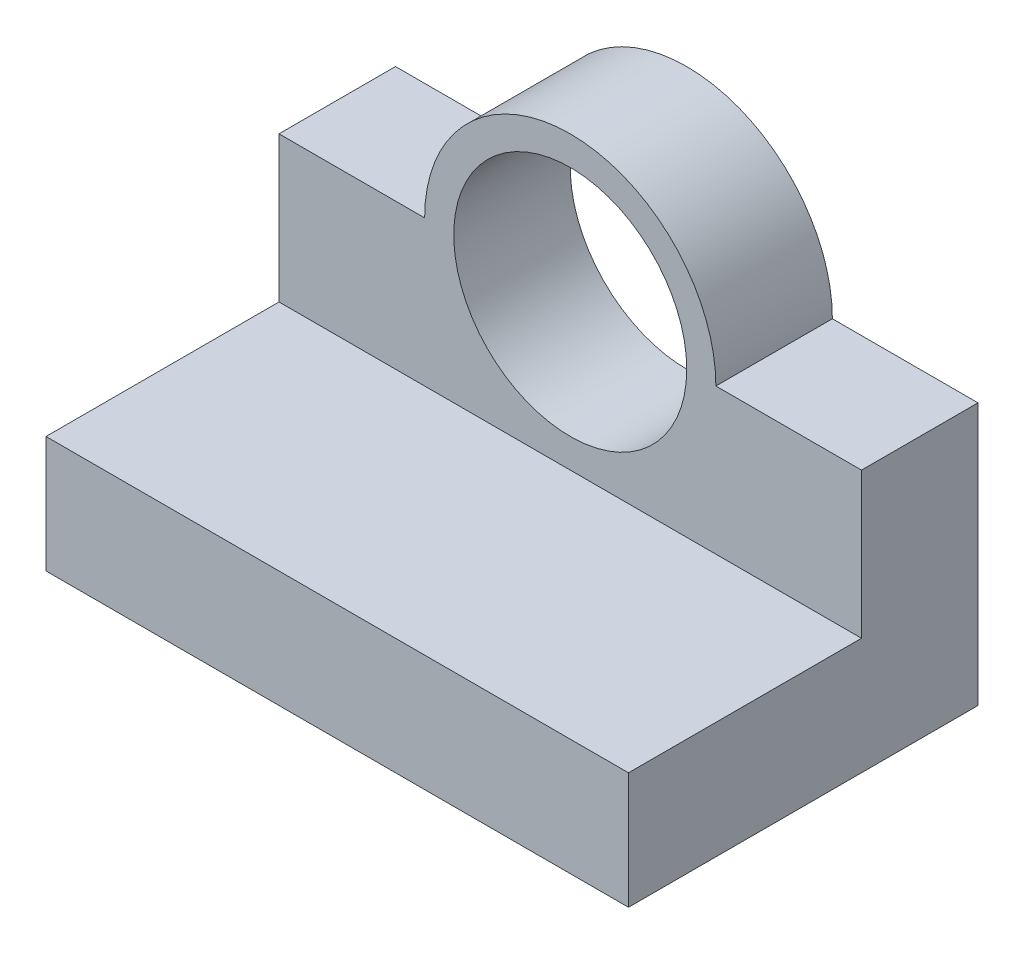
SolidWorks part; units mm, degrees
ref_plane "Front Plane" through (0, 0, 0) normal (0, 0, 1) x (1, 0, 0)
ref_plane "Top Plane" through (0, 0, 0) normal (0, 1, 0) x (1, 0, 0)
ref_plane "Right Plane" through (0, 0, 0) normal (1, 0, 0) x (0, 0, -1)
sketch "Sketch2" plane through (0, 0, 0) normal (0, 1, 0) x (1, 0, 0)
  line L1 (-50, 30) -> (50, 30)
  line L2 (-50, 30) -> (-50, -30)
  line L3 (-50, -30) -> (50, -30)
  line L4 (50, 30) -> (50, -30)
  line L5 (-50, 30) -> (50, -30) construction
  line L6 (-50, -30) -> (50, 30) construction
  point P0 (0, 0)
  dimension "D1" = 60
  dimension "D2" = 100
extrude "Boss-Extrude1" add sketch "Sketch2" along normal blind 20
sketch "Sketch3" plane through (0, 20, 0) normal (0, 1, 0) x (1, 0, 0)
  line L0 (-50, 20) -> (50, 20) construction
  line L1 (-50, 30) -> (-50, -30) construction
  line L2 (50, -30) -> (50, 30) construction
  line L3 (50, 30) -> (-50, 30) construction
  line L5 (-50, 10) -> (50, 10)
  line L6 (-50, 10) -> (-50, 30)
  line L7 (-50, 30) -> (50, 30)
  line L8 (50, 10) -> (50, 30)
  line L9 (-50, 10) -> (50, 30) construction
  line L10 (-50, 30) -> (50, 10) construction
  point P8 (0, 20)
  dimension "D1" = 10
extrude "Boss-Extrude2" add sketch "Sketch3" along normal blind 25
sketch "Sketch4" plane through (0, 0, -10) normal (0, 0, 1) x (1, 0, 0)
  line L0 (-50, 45) -> (50, 45) construction
  circle A0 centre (0, 45) radius 25
  circle A1 centre (0, 45) radius 20
extrude "Boss-Extrude3" add sketch "Sketch4" against normal up to surface (20 mm away) up to face at (0, 22.5, -30)
sketch "Sketch5" plane through (0, 0, -10) normal (0, 0, 1) x (1, 0, 0)
  line L0 (-20, 45) -> (20, 45) construction
  circle A0 centre (0, 45) radius 20
extrude "Cut-Extrude2" cut sketch "Sketch5" against normal up to surface (20 mm away) up to face at (0, 34.1667, -30)
